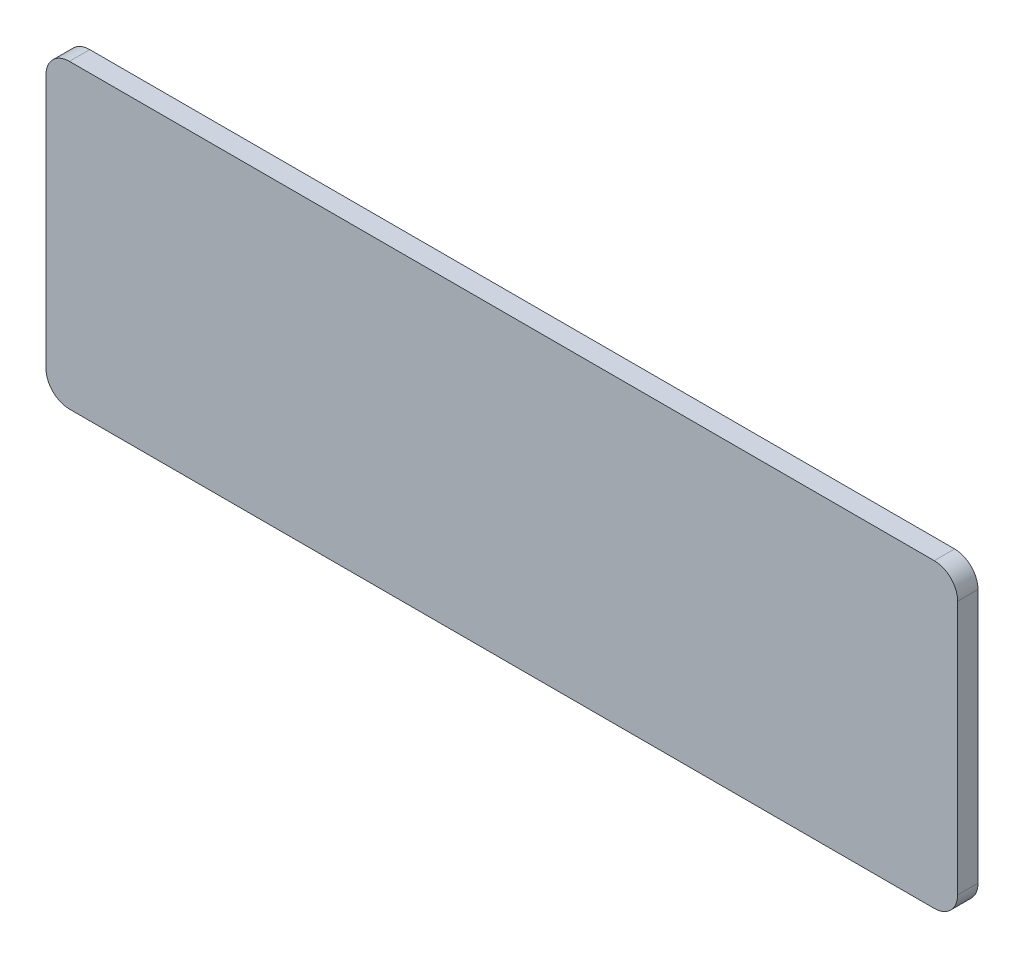
SolidWorks part; units mm, degrees
ref_plane "Front Plane" through (0, 0, 0) normal (0, 0, 1) x (1, 0, 0)
ref_plane "Top Plane" through (0, 0, 0) normal (0, 1, 0) x (1, 0, 0)
ref_plane "Right Plane" through (0, 0, 0) normal (1, 0, 0) x (0, 0, -1)
sketch "Model" plane through (0, 0, 0) normal (0, 0, 1) x (1, 0, 0)
  line L0 (11.938, 256.6179) -> (11.938, 224.8679)
  line L1 (15.113, 221.6929) -> (123.063, 221.6929)
  line L2 (126.238, 224.8679) -> (126.238, 256.6179)
  line L3 (123.063, 259.7929) -> (15.113, 259.7929)
  arc A0 (15.113, 259.7929) -> (11.938, 256.6179) centre (15.113, 256.6179) ccw
  arc A1 (11.938, 224.8679) -> (15.113, 221.6929) centre (15.113, 224.8679) ccw
  arc A2 (123.063, 221.6929) -> (126.238, 224.8679) centre (123.063, 224.8679) ccw
  arc A3 (126.238, 256.6179) -> (123.063, 259.7929) centre (123.063, 256.6179) ccw
sketch "Sketch2" plane through (0, 0, 0) normal (0, 0, 1) x (1, 0, 0)
  line L8 (123.063, 259.5389) -> (15.113, 259.5389)
  line L9 (12.192, 256.6179) -> (12.192, 224.8679)
  line L10 (15.113, 221.9469) -> (123.063, 221.9469)
  line L11 (125.984, 224.8679) -> (125.984, 256.6179)
  line L12 (123.063, 259.5389) -> (15.113, 259.5389)
  line L13 (12.192, 256.6179) -> (12.192, 224.8679)
  line L14 (15.113, 221.9469) -> (123.063, 221.9469)
  line L15 (125.984, 224.8679) -> (125.984, 256.6179)
  arc A8 (15.113, 259.5389) -> (12.192, 256.6179) centre (15.113, 256.6179) ccw
  arc A9 (12.192, 224.8679) -> (15.113, 221.9469) centre (15.113, 224.8679) ccw
  arc A10 (123.063, 221.9469) -> (125.984, 224.8679) centre (123.063, 224.8679) ccw
  arc A11 (125.984, 256.6179) -> (123.063, 259.5389) centre (123.063, 256.6179) ccw
  arc A12 (15.113, 259.5389) -> (12.192, 256.6179) centre (15.113, 256.6179) ccw
  arc A13 (12.192, 224.8679) -> (15.113, 221.9469) centre (15.113, 224.8679) ccw
  arc A14 (123.063, 221.9469) -> (125.984, 224.8679) centre (123.063, 224.8679) ccw
  arc A15 (125.984, 256.6179) -> (123.063, 259.5389) centre (123.063, 256.6179) ccw
  dimension "D1" = 0.254
extrude "Boss-Extrude1" add sketch "Sketch2" along normal blind 2.54
